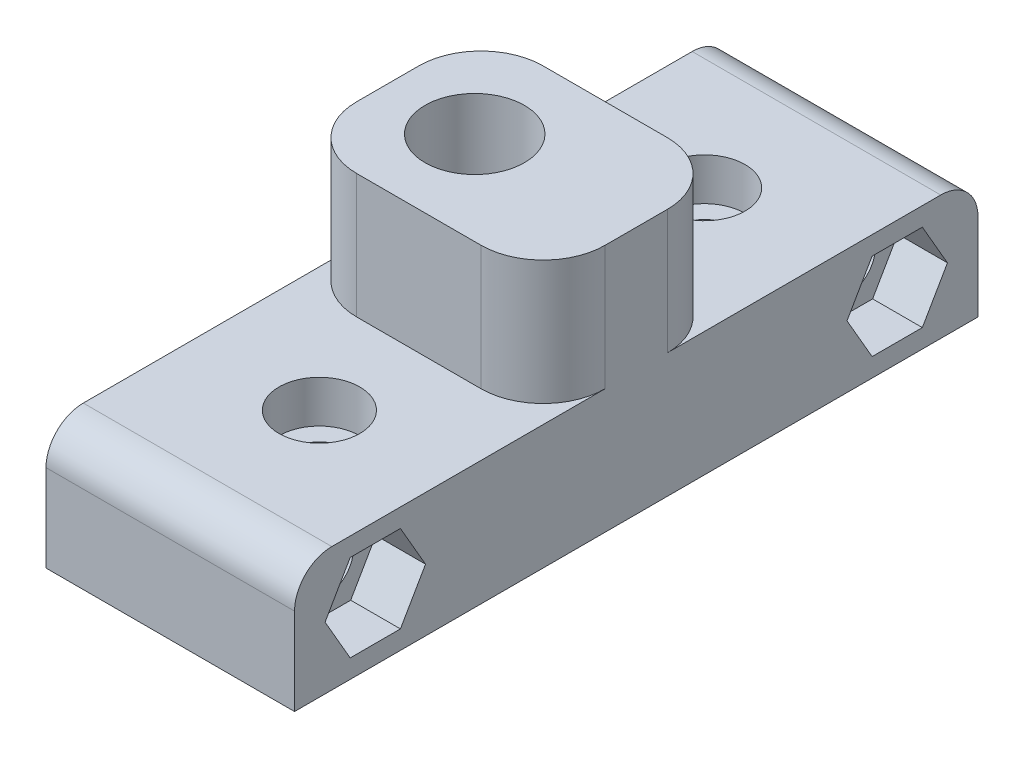
SolidWorks part; units mm, degrees
material "ABS"
ref_plane "Front Plane" through (0, 0, 0) normal (0, 0, 1) x (1, 0, 0)
ref_plane "Top Plane" through (0, 0, 0) normal (0, 1, 0) x (1, 0, 0)
ref_plane "Right Plane" through (0, 0, 0) normal (1, 0, 0) x (0, 0, -1)
sketch "Sketch1" plane through (0, 0, 0) normal (0, 1, 0) x (1, 0, 0)
  line L1 (-10, -27.5) -> (10, -27.5)
  line L2 (-10, -27.5) -> (-10, 27.5)
  line L3 (-10, 27.5) -> (10, 27.5)
  line L4 (10, -27.5) -> (10, 27.5)
  line L5 (-10, -27.5) -> (10, 27.5) construction
  line L6 (-10, 27.5) -> (10, -27.5) construction
  point P1 (0, 0)
  dimension "D1" = 20
  dimension "D2" = 55
extrude "Boss-Extrude1" add sketch "Sketch1" along normal blind 20
sketch "Sketch2" plane through (0, 20, 0) normal (0, 1, 0) x (1, 0, 0)
  line L0 (-10, 27.5) -> (-10, -27.5) construction
  circle A0 centre (-3, 0) radius 4
  dimension "D2" = 8
  dimension "D1" = 7
extrude "Cut-Extrude1" cut sketch "Sketch2" against normal blind 10
sketch "Sketch3" plane through (0, 20, 0) normal (0, 1, 0) x (1, 0, 0)
  line L0 (10, -27.5) -> (10, 27.5) construction
  line L1 (-10, -27.5) -> (10, -27.5)
  line L2 (-10, -27.5) -> (-10, -7.5)
  line L3 (-10, -7.5) -> (10, -7.5)
  line L4 (10, -27.5) -> (10, -7.5)
  line L6 (-10, 27.5) -> (10, 27.5)
  line L7 (-10, 27.5) -> (-10, 7.5)
  line L8 (-10, 7.5) -> (10, 7.5)
  line L9 (10, 27.5) -> (10, 7.5)
  dimension "D1" = 20
  dimension "D2" = 20
extrude "Cut-Extrude2" cut sketch "Sketch3" against normal blind 10
sketch "Sketch6" plane through (0, 0, 0) normal (0, -1, 0) x (1, 0, 0)
  line L0 (10, 27.5) -> (10, -27.5) construction
  line L1 (-10, 27.5) -> (10, 27.5)
  line L2 (-10, 27.5) -> (-10, -27.5)
  line L3 (-10, -27.5) -> (10, -27.5)
  line L4 (10, 27.5) -> (10, -27.5)
  line L5 (-10, 27.5) -> (10, -27.5) construction
  line L6 (-10, -27.5) -> (10, 27.5) construction
  point P0 (0, 0)
  dimension "D1" = 55
extrude "Boss-Extrude2" [suppressed] add sketch "Sketch6" along normal blind 10
hole_wizard "CBORE for M3 Hex Socket Head Cap Screw1" positions "Sketch4" profile "Sketch5" counterbore size "M3" standard "ISO" end condition through all
sketch "Sketch4" plane through (0, 10, 0) normal (0, 1, 0) x (1, 0, 0)
  line L1 (-10, -27.5) -> (10, -27.5) construction
  line L2 (10, 27.5) -> (-10, 27.5) construction
  point P0 (0, -15.5)
  point P2 (0, 15.5)
  dimension "D1" = 12
  dimension "D2" = 12
sketch "Sketch5" plane through (0, 10, 15.5) normal (1, 0, 0) x (0, 0, 1)
  line L0 (0, 0) -> (0, 10)
  line L1 (0, 10) -> (1.7, 10)
  line L3 (1.7, 10) -> (1.7, 3.4)
  line L4 (1.7, 3.4) -> (3.25, 3.4)
  line L5 (3.25, 3.4) -> (3.25, 0)
  line L7 (3.25, 0) -> (0, 0)
  line L11 (0, -6.35) -> (0, 107.95) construction
  dimension "Thru Hole Dia." = 3.4
  dimension "Thru Hole Depth" = 10
  dimension "C'Bore Dia." = 6.5
  dimension "C'Bore Depth" = 3.4
fillet "Fillet2" radius 5 4 edges at (-10, 15, -7.5) (-10, 15, 7.5) (10, 15, -7.5) (10, 15, 7.5)
sketch "Sketch7" [suppressed] plane through (10, 0, 0) normal (1, 0, 0) x (0, 0, -1)
  line L0 (27.5, -10) -> (-27.5, -10) construction
  line L1 (-27.5, -10) -> (-27.5, 0) construction
  circle A0 centre (-21, -5) radius 2.25
  circle A1 centre (21, -5) radius 2.25
  dimension "D1" = 4.5
  dimension "D4" = 4.5
  dimension "D2" = 5
  dimension "D3" = 6.5
  dimension "D5" = 42
extrude "Cut-Extrude3" [suppressed] cut sketch "Sketch7" against normal through all
sketch "Sketch8" [suppressed] plane through (10, 0, 0) normal (1, 0, 0) x (0, 0, -1)
  line L1 (-16.7276, -5) -> (-18.8638, -1.3)
  line L2 (-18.8638, -1.3) -> (-23.1362, -1.3)
  line L3 (-23.1362, -1.3) -> (-25.2724, -5)
  line L4 (-25.2724, -5) -> (-23.1362, -8.7)
  line L5 (-23.1362, -8.7) -> (-18.8638, -8.7)
  line L6 (-18.8638, -8.7) -> (-16.7276, -5)
  line L7 (16.7276, -5) -> (18.8638, -8.7)
  line L8 (18.8638, -8.7) -> (23.1362, -8.7)
  line L9 (23.1362, -8.7) -> (25.2724, -5)
  line L10 (25.2724, -5) -> (23.1362, -1.3)
  line L11 (23.1362, -1.3) -> (18.8638, -1.3)
  line L12 (18.8638, -1.3) -> (16.7276, -5)
  circle A0 centre (-21, -5) radius 3.7 construction
  circle A1 centre (21, -5) radius 3.7 construction
  dimension "D1" = 7.4
  dimension "D2" = 7.4
extrude "Cut-Extrude4" [suppressed] cut sketch "Sketch8" against normal blind 4
fillet "Fillet3" [suppressed] radius 5
fillet "Fillet4" [suppressed] radius 5
sketch "Sketch9" plane through (-10, 0, 0) normal (-1, 0, 0) x (0, 0, 1)
  line L0 (-27.5, 0) -> (27.5, 0) construction
  line L1 (-27.5, 10) -> (-27.5, 0) construction
  circle A0 centre (-21, 5) radius 2.25
  circle A1 centre (21, 5) radius 2.25
  dimension "D2" = 4.5
  dimension "D5" = 4.5
  dimension "D1" = 5
  dimension "D3" = 6.5
  dimension "D4" = 42
extrude "Cut-Extrude5" cut sketch "Sketch9" against normal through all
sketch "Sketch10" plane through (10, 0, 0) normal (1, 0, 0) x (0, 0, -1)
  line L1 (-16.9585, 5) -> (-18.9793, 8.5)
  line L2 (-18.9793, 8.5) -> (-23.0207, 8.5)
  line L3 (-23.0207, 8.5) -> (-25.0415, 5)
  line L4 (-25.0415, 5) -> (-23.0207, 1.5)
  line L5 (-23.0207, 1.5) -> (-18.9793, 1.5)
  line L6 (-18.9793, 1.5) -> (-16.9585, 5)
  line L7 (16.9585, 5) -> (18.9793, 1.5)
  line L8 (18.9793, 1.5) -> (23.0207, 1.5)
  line L9 (23.0207, 1.5) -> (25.0415, 5)
  line L10 (25.0415, 5) -> (23.0207, 8.5)
  line L11 (23.0207, 8.5) -> (18.9793, 8.5)
  line L12 (18.9793, 8.5) -> (16.9585, 5)
  circle A0 centre (-21, 5) radius 3.5 construction
  circle A1 centre (21, 5) radius 3.5 construction
  dimension "D1" = 7
  dimension "D2" = 7
extrude "Cut-Extrude6" cut sketch "Sketch10" against normal blind 4
fillet "Fillet5" radius 3 2 edges at (0, 10, 27.5) (0, 10, -27.5)
